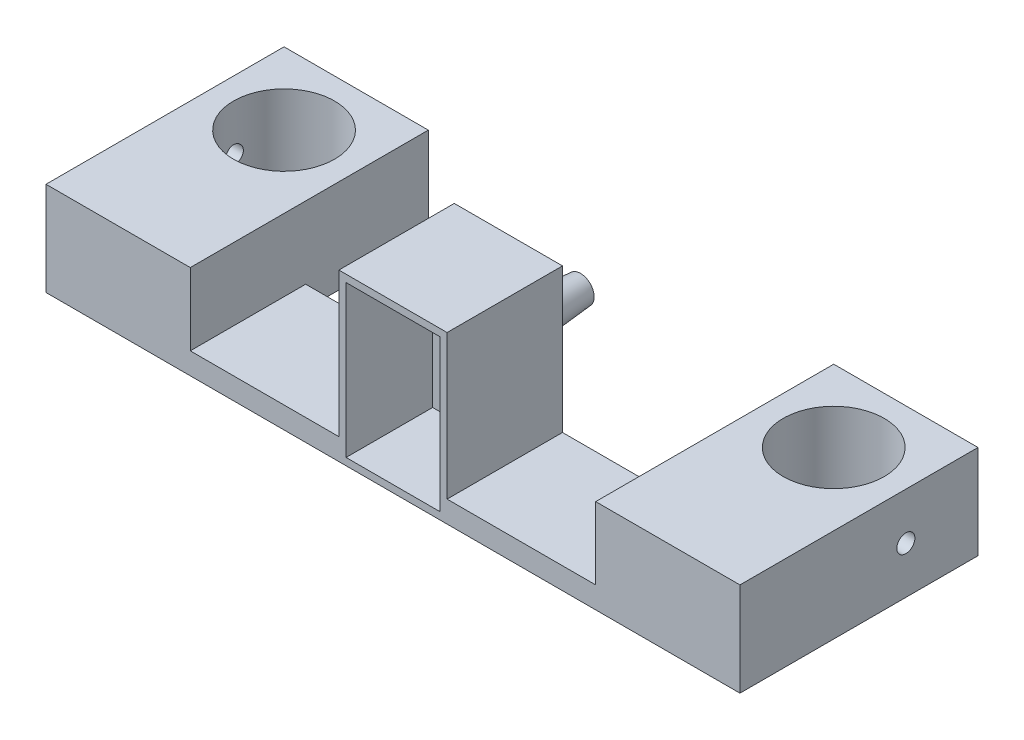
SolidWorks part; units mm, degrees
ref_plane "Front Plane" through (0, 0, 0) normal (0, 0, 1) x (1, 0, 0)
ref_plane "Top Plane" through (0, 0, 0) normal (0, 1, 0) x (1, 0, 0)
ref_plane "Right Plane" through (0, 0, 0) normal (1, 0, 0) x (0, 0, -1)
sketch "Sketch1" plane through (0, 0, 0) normal (0, 1, 0) x (1, 0, 0)
  line L0 (31.1, 0) -> (28.1, 0) construction
  line L1 (38.1, 7) -> (38.1, 10) construction
  line L2 (-38.1, 7) -> (-38.1, 10) construction
  line L3 (-45.1, 0) -> (-48.1, 0) construction
  line L4 (-31.1, 0) -> (-28.1, 0) construction
  line L5 (45.1, 0) -> (48.1, 0) construction
  line L6 (-38.1, -7) -> (-38.1, -23) construction
  line L11 (38.1, -7) -> (38.1, -23) construction
  line L12 (-28.1, -7) -> (-28.1, 10)
  line L13 (-48.1, 10) -> (-28.1, 10)
  line L14 (-48.1, 10) -> (-48.1, -23)
  line L15 (-48.1, -23) -> (-28.1, -23)
  line L17 (28.1, 10) -> (48.1, 10)
  line L19 (28.1, -23) -> (48.1, -23)
  line L20 (48.1, 10) -> (48.1, -23)
  line L21 (-28.1, -7) -> (28.1, -7)
  line L23 (-28.1, -23) -> (28.1, -23)
  line L25 (28.1, 10) -> (28.1, -7)
  circle A0 centre (-38.1, 0) radius 7
  circle A1 centre (38.1, 0) radius 7
extrude "Boss-Extrude1" add sketch "Sketch1" along normal blind 13
sketch "Sketch2" plane through (0, 13, 0) normal (0, 1, 0) x (1, 0, 0)
  line L0 (-48.1, -23) -> (48.1, -23) construction
  line L1 (-28.1, -7) -> (28.1, -7)
  line L2 (-28.1, -7) -> (-28.1, -23)
  line L3 (-28.1, -23) -> (28.1, -23)
  line L4 (28.1, -7) -> (28.1, -23)
extrude "Cut-Extrude1" cut sketch "Sketch2" against normal blind 10
sketch "Sketch3" plane through (0, 3, 0) normal (0, 1, 0) x (1, 0, 0)
  line L0 (0, -7) -> (7.5, -7) construction
  line L1 (28.1, -7) -> (-28.1, -7) construction
  line L2 (0, -7) -> (-7.5, -7) construction
  line L3 (-28.1, -23) -> (28.1, -23) construction
  line L4 (-7.5, -7) -> (7.5, -7)
  line L5 (-7.5, -7) -> (-7.5, -23)
  line L6 (-7.5, -23) -> (7.5, -23)
  line L7 (7.5, -7) -> (7.5, -23)
extrude "Cut-Extrude2" cut sketch "Sketch3" against normal up to next
sketch "Sketch4" plane through (0, 0, 23) normal (0, 0, 1) x (1, 0, 0)
  line L0 (7.5, 0) -> (7.5, 3) construction
  line L1 (-7.5, 0) -> (7.5, 0)
  line L2 (-7.5, 0) -> (-7.5, 23)
  line L3 (-7.5, 23) -> (7.5, 23)
  line L4 (7.5, 0) -> (7.5, 23)
extrude "Boss-Extrude2" add sketch "Sketch4" against normal blind 16
sketch "Sketch5" plane through (0, 0, 23) normal (0, 0, 1) x (1, 0, 0)
  line L0 (0, 23) -> (0, 22) construction
  line L1 (7.5, 23) -> (-7.5, 23) construction
  line L2 (0, 0) -> (0, 1) construction
  line L3 (-7.5, 13) -> (-6.5, 13) construction
  line L4 (-7.5, 23) -> (-7.5, 3) construction
  line L5 (7.5, 13) -> (6.5, 13) construction
  line L6 (7.5, 3) -> (7.5, 23) construction
  line L12 (-6.5, 22) -> (6.5, 22)
  line L13 (-6.5, 22) -> (-6.5, 1)
  line L14 (-6.5, 1) -> (6.5, 1)
  line L15 (6.5, 22) -> (6.5, 1)
extrude "Cut-Extrude3" cut sketch "Sketch5" against normal blind 12
sketch "Sketch6" plane through (0, 0, 11) normal (0, 0, 1) x (1, 0, 0)
  line L0 (0, 11.4642) -> (0, 6.9642) construction
  circle A0 centre (0, 11.4642) radius 1.5
  circle A1 centre (0, 6.9642) radius 1.05
extrude "Cut-Extrude4" cut sketch "Sketch6" against normal up to next
sketch "Sketch7" plane through (0, 0, 7) normal (0, 0, -1) x (-1, 0, 0)
  circle A0 centre (0, 11.4642) radius 2.5
  circle A2 centre (0, 11.4642) radius 1.5
extrude "Boss-Extrude3" add sketch "Sketch7" along normal blind 10
chamfer "Chamfer1" distance 7 angle 5 1 edges at (-2.5, 11.4642, -3)
sketch "Sketch8" plane through (-48.1, 0, 0) normal (-1, 0, 0) x (0, 0, 1)
  circle A0 centre (0, 6.5) radius 1.25
extrude "Cut-Extrude5" cut sketch "Sketch8" against normal up to next
sketch "Sketch9" plane through (48.1, 0, 0) normal (1, 0, 0) x (0, 0, -1)
  circle A0 centre (0, 6.5) radius 1.25
extrude "Cut-Extrude6" cut sketch "Sketch9" against normal up to next
